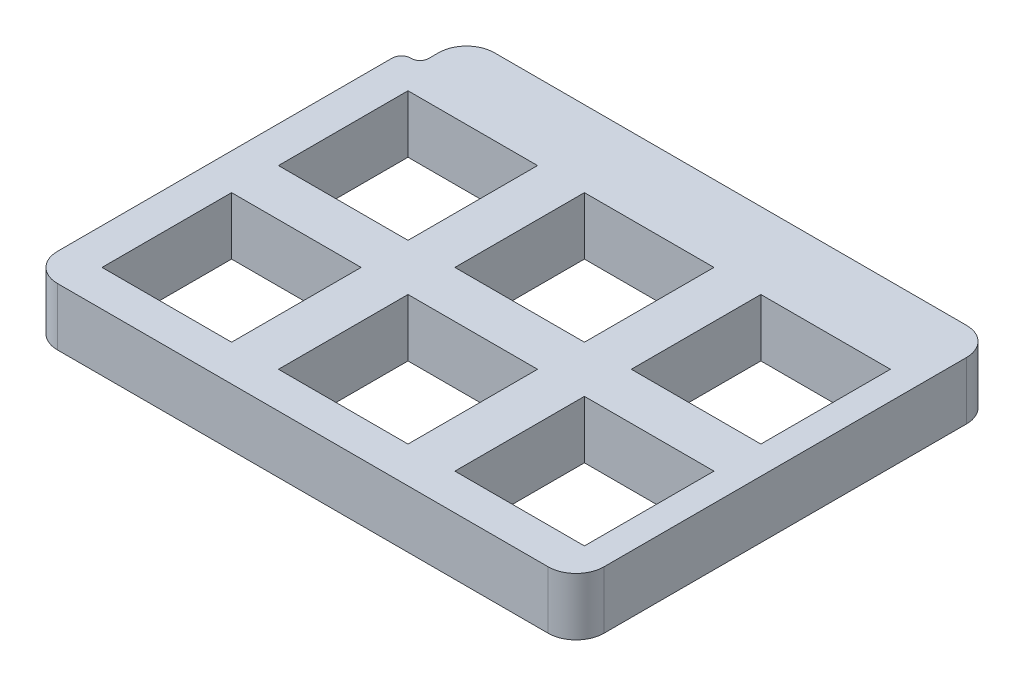
SolidWorks part; units mm, degrees
material "PMMA"
ref_plane "Front Plane" through (0, 0, 0) normal (0, 0, 1) x (1, 0, 0)
ref_plane "Top Plane" through (0, 0, 0) normal (0, 1, 0) x (1, 0, 0)
ref_plane "Right Plane" through (0, 0, 0) normal (1, 0, 0) x (0, 0, -1)
sketch "Sketch1" plane through (0, 0, 0) normal (0, 1, 0) x (1, 0, 0)
  line L0 (22.9, -8.2) -> (22.9, -22.15)
  line L1 (5, 0) -> (55.85, 0)
  line L2 (0, -6) -> (0, -42.05)
  line L3 (3, -45.05) -> (55.85, -45.05)
  line L4 (58.85, -3) -> (58.85, -42.05)
  line L5 (3.9, -8.2) -> (17.85, -8.2)
  line L6 (3.9, -8.2) -> (3.9, -22.15)
  line L7 (3.9, -22.15) -> (17.85, -22.15)
  line L8 (17.85, -8.2) -> (17.85, -22.15)
  line L9 (22.9, -8.2) -> (36.85, -8.2)
  line L10 (36.85, -8.2) -> (36.85, -22.15)
  line L11 (22.9, -22.15) -> (36.85, -22.15)
  line L12 (41.9, -8.2) -> (41.9, -22.15)
  line L13 (41.9, -8.2) -> (55.85, -8.2)
  line L14 (55.85, -8.2) -> (55.85, -22.15)
  line L15 (41.9, -22.15) -> (55.85, -22.15)
  line L16 (22.9, -27.2) -> (22.9, -41.15)
  line L17 (22.9, -27.2) -> (36.85, -27.2)
  line L18 (36.85, -27.2) -> (36.85, -41.15)
  line L19 (22.9, -41.15) -> (36.85, -41.15)
  line L20 (41.9, -27.2) -> (41.9, -41.15)
  line L21 (41.9, -27.2) -> (55.85, -27.2)
  line L22 (55.85, -27.2) -> (55.85, -41.15)
  line L23 (41.9, -41.15) -> (55.85, -41.15)
  line L24 (3.9, -27.2) -> (3.9, -41.15)
  line L25 (3.9, -27.2) -> (17.85, -27.2)
  line L26 (17.85, -27.2) -> (17.85, -41.15)
  line L27 (3.9, -41.15) -> (17.85, -41.15)
  line L30 (1, -5) -> (1.1, -5)
  line L31 (2, -4.1) -> (2, -3)
  arc A0 (58.85, -3) -> (55.85, 0) centre (55.85, -3) ccw
  arc A1 (55.85, -45.05) -> (58.85, -42.05) centre (55.85, -42.05) ccw
  arc A2 (0, -42.05) -> (3, -45.05) centre (3, -42.05) ccw
  arc A3 (1, -5) -> (0, -6) centre (1, -6) ccw
  arc A4 (2, -3) -> (5, 0) centre (5, -3) cw
  arc A5 (1.1, -5) -> (2, -4.1) centre (1.1, -4.1) ccw
  point P9 (10.875, -27.2)
  point P37 (0, -5)
  point P38 (0, 0)
  point P44 (2, 0)
  point P47 (2, -5)
  dimension "D11" = 3
  dimension "D12" = 3
  dimension "D13" = 3
  dimension "D14" = 1
  dimension "D17" = 3
  dimension "D18" = 0.9
  dimension "D1" = 13.95
  dimension "D2" = 13.95
  dimension "D5" = 8.2
  dimension "D6" = 3.9
  dimension "D7" = 3
  dimension "D8" = 5.05
  dimension "D9" = 3.9
  dimension "D10" = 5.05
  dimension "D15" = 5
  dimension "D16" = 2
  dimension "D3" = 3
  dimension "D4" = 2
extrude "Boss-Extrude1" add sketch "Sketch1" along normal blind 6.2
